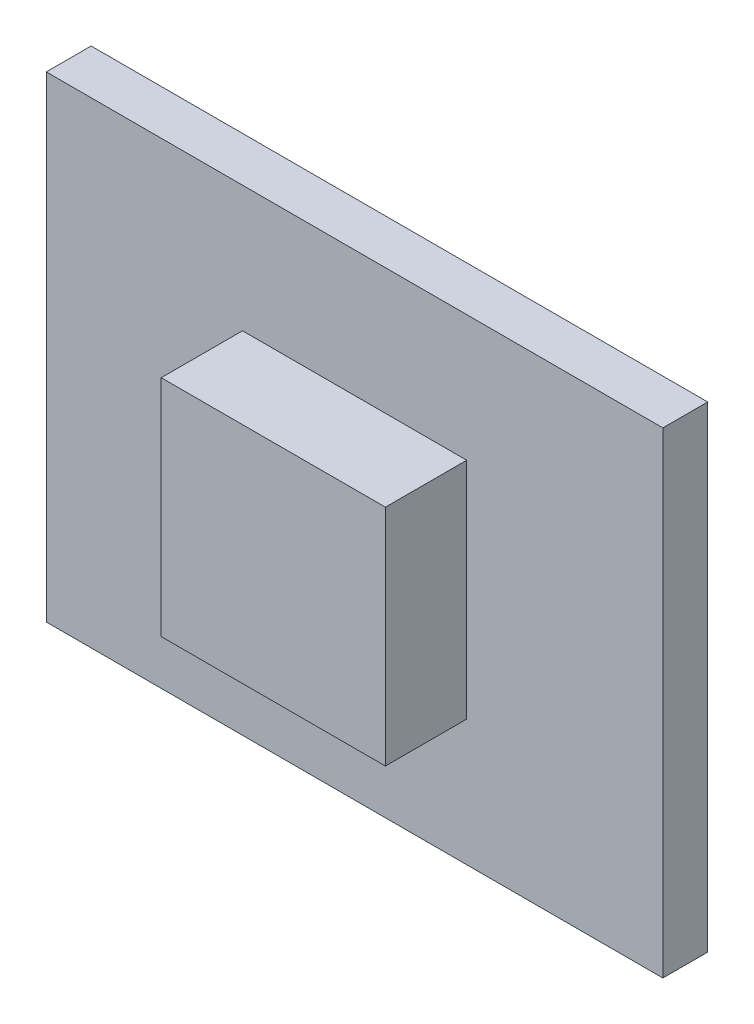
SolidWorks part; units mm, degrees
ref_plane "Front Plane" through (0, 0, 0) normal (0, 0, 1) x (1, 0, 0)
ref_plane "Top Plane" through (0, 0, 0) normal (0, 1, 0) x (1, 0, 0)
ref_plane "Right Plane" through (0, 0, 0) normal (1, 0, 0) x (0, 0, -1)
sketch "Sketch1" plane through (0, 0, 0) normal (0, 0, 1) x (1, 0, 0)
  line L0 (-11, -8.5) -> (11, -8.5)
  line L1 (11, -8.5) -> (11, 8.5)
  line L2 (11, 8.5) -> (-11, 8.5)
  line L3 (-11, 8.5) -> (-11, -8.5)
extrude "PCB" add sketch "Sketch1" along normal blind 1.6
ref_plane "P_Front_1p6" through (0, 0, 1.6) normal (0, 0, 1) x (1, 0, 0)
sketch "Sketch2" plane through (0, 0, 1.6) normal (0, 0, 1) x (1, 0, 0)
  line L0 (-4, -4) -> (4, -4)
  line L1 (4, -4) -> (4, 4)
  line L2 (4, 4) -> (-4, 4)
  line L3 (-4, 4) -> (-4, -4)
extrude "Inductor" add sketch "Sketch2" along normal blind 2.9
